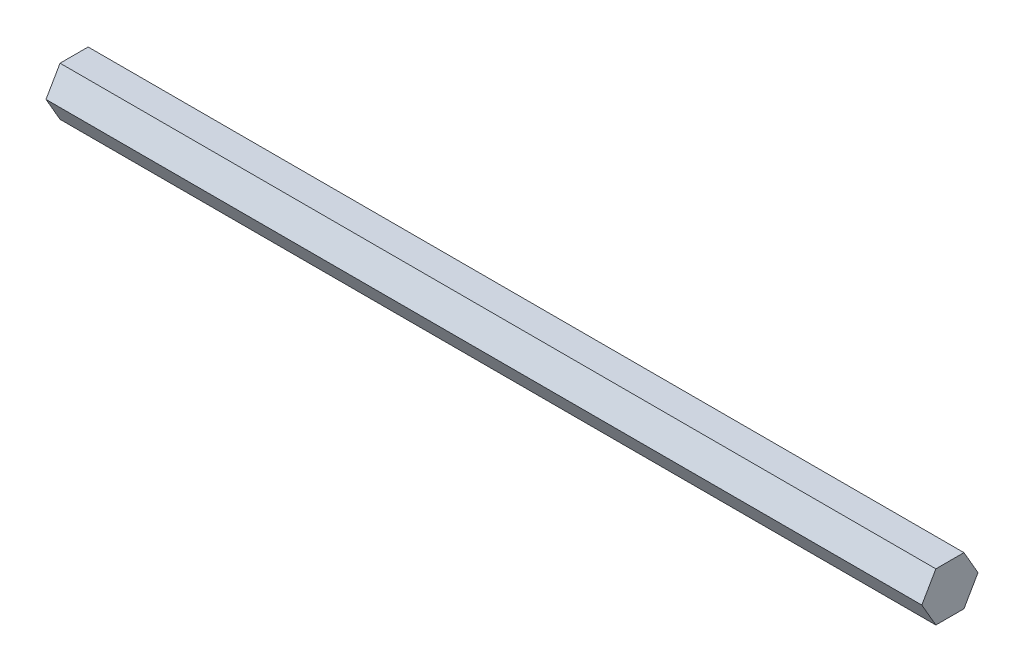
SolidWorks part; units mm, degrees
ref_plane "Front Plane" through (0, 0, 0) normal (0, 0, 1) x (1, 0, 0)
ref_plane "Top Plane" through (0, 0, 0) normal (0, 1, 0) x (1, 0, 0)
ref_plane "Right Plane" through (0, 0, 0) normal (1, 0, 0) x (0, 0, -1)
ref_plane "Plane1" through (0, 0, 0) normal (-1, 0, 0) x (0, -1, 0)
sketch "Sketch1" plane through (0, 0, 0) normal (-1, 0, 0) x (0, -1, 0)
  line L0 (0, 7.3323) -> (-6.35, 3.6662)
  line L1 (-6.35, 3.6662) -> (-6.35, -3.6662)
  line L2 (-6.35, -3.6662) -> (0, -7.3323)
  line L3 (0, -7.3323) -> (6.35, -3.6662)
  line L4 (6.35, -3.6662) -> (6.35, 3.6662)
  line L5 (6.35, 3.6662) -> (0, 7.3323)
extrude "Boss-Extrude1" add sketch "Sketch1" against normal blind 228.6
